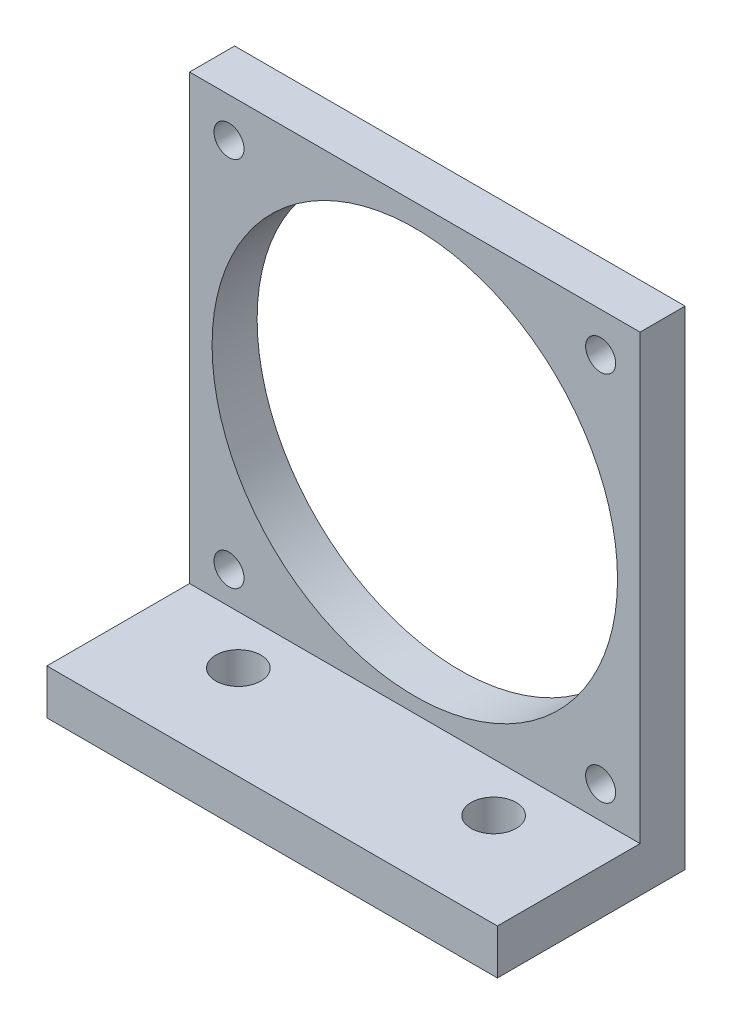
SolidWorks part; units mm, degrees
ref_plane "前基準面" through (0, 0, 0) normal (0, 0, 1) x (1, 0, 0)
ref_plane "上基準面" through (0, 0, 0) normal (0, 1, 0) x (1, 0, 0)
ref_plane "右基準面" through (0, 0, 0) normal (1, 0, 0) x (0, 0, -1)
sketch "草圖1" plane through (0, 0, 0) normal (0, 0, 1) x (1, 0, 0)
  line L1 (0, 0) -> (60, 0)
  line L2 (0, 0) -> (0, 65)
  line L3 (0, 65) -> (60, 65)
  line L4 (60, 0) -> (60, 65)
  dimension "D1" = 60
  dimension "D2" = 65
extrude "填料-伸長1" add sketch "草圖1" along normal blind 6
sketch "草圖2" plane through (0, 0, 6) normal (0, 0, 1) x (1, 0, 0)
  line L1 (0, 0) -> (60, 0)
  line L2 (0, 0) -> (0, 6)
  line L3 (0, 6) -> (60, 6)
  line L4 (60, 0) -> (60, 6)
  dimension "D1" = 60
  dimension "D2" = 6
extrude "填料-伸長2" add sketch "草圖2" along normal blind 19
sketch "草圖3" plane through (0, 0, 0) normal (0, 0, -1) x (-1, 0, 0)
  line L0 (0, 0) -> (-60, 0) construction
  line L1 (-60, 6) -> (-60, 65) construction
  line L3 (-54.7487, 59.7487) -> (-5.2513, 59.7487) construction
  line L4 (-54.7487, 59.7487) -> (-54.7487, 10.2513) construction
  line L5 (-54.7487, 10.2513) -> (-5.2513, 10.2513) construction
  line L6 (-5.2513, 59.7487) -> (-5.2513, 10.2513) construction
  circle A0 centre (-30, 35) radius 27
  circle A1 centre (-30, 35) radius 35 construction
  circle A2 centre (-54.7487, 59.7487) radius 2
  circle A3 centre (-5.2513, 59.7487) radius 2
  circle A4 centre (-54.7487, 10.2513) radius 2
  circle A5 centre (-5.2513, 10.2513) radius 2
  dimension "D1" = 35
  dimension "D2" = 54
  dimension "D3" = 30
  dimension "D4" = 70
  dimension "D5" = 4
  dimension "D6" = 4
  dimension "D7" = 4
  dimension "D8" = 4
sketch "草圖4" plane through (0, 0, 0) normal (0, -1, 0) x (-1, 0, 0)
  line L0 (0, -12.5) -> (-60, -12.5) construction
  line L1 (0, -25) -> (0, 0) construction
  line L2 (-60, -25) -> (-60, 0) construction
  circle A0 centre (-13, -12.5) radius 3
  circle A1 centre (-47, -12.5) radius 3
  dimension "D1" = 6
  dimension "D2" = 13
  dimension "D3" = 2
extrude "除料-伸長2" cut sketch "草圖4" against normal up to next
extrude "除料-伸長3" cut sketch "草圖3" against normal up to next
